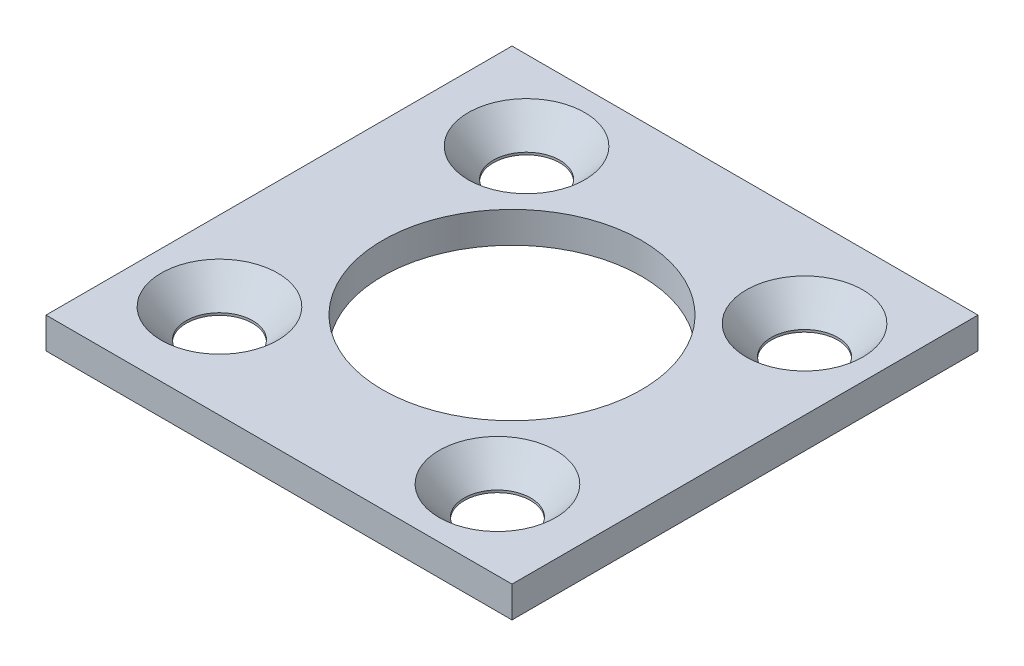
SolidWorks part; units mm, degrees
material "6061-T6 (SS)"
ref_plane "Front Plane" through (0, 0, 0) normal (0, 0, 1) x (1, 0, 0)
ref_plane "Top Plane" through (0, 0, 0) normal (0, 1, 0) x (1, 0, 0)
ref_plane "Right Plane" through (0, 0, 0) normal (1, 0, 0) x (0, 0, -1)
sketch "Sketch1" plane through (0, 0, 0) normal (0, 1, 0) x (1, 0, 0)
  line L1 (0, 0) -> (-22.86, 0)
  line L2 (0, 0) -> (0, 22.86)
  line L3 (0, 22.86) -> (-22.86, 22.86)
  line L4 (-22.86, 0) -> (-22.86, 22.86)
  circle A0 centre (-11.43, 11.43) radius 6.35
  point P9 (-24.5662, 22.7018)
  dimension "D5" = 12.7
  dimension "D1" = 22.86
  dimension "D2" = 22.86
  dimension "D3" = 11.43
  dimension "D4" = 11.43
extrude "Boss-Extrude1" add sketch "Sketch1" along normal blind 1.524
hole_wizard "CSK for #4 Flat Head Machine Screw1" positions "Sketch4" profile "Sketch3" countersink size "#4" standard "ANSI Inch" end condition through all
sketch "Sketch4" plane through (0, 1.524, 0) normal (0, 1, 0) x (1, 0, 0)
  point P0 (-3.8977, 18.2484)
  point P3 (-4.6116, 3.8977)
  point P6 (-18.9623, 4.6116)
  point P9 (-18.2484, 18.9623)
sketch "Sketch3" plane through (-3.8977, 1.524, -18.2484) normal (1, 0, 0) x (0, 0, 1)
  line L0 (0, 0) -> (0, 1.524)
  line L1 (0, 1.524) -> (1.6319, 1.524)
  line L2 (1.6319, 1.524) -> (1.6319, 1.4098)
  line L3 (1.6319, 1.4098) -> (2.8575, 0)
  line L5 (2.8575, 0) -> (0, 0)
  line L6 (-1.6319, 1.4098) -> (-2.8575, 0) construction
  line L11 (0, -6.35) -> (0, 107.95) construction
  dimension "Thru Hole Dia." = 3.2639
  dimension "Thru Hole Depth" = 1.524
  dimension "Near C'Sink Dia." = 5.715
  dimension "Near C'Sink Angle" = 82
equation "\"D3@Sketch1\"=\"D2@Sketch1\"/2"
equation "\"D4@Sketch1\"=\"D1@Sketch1\"/2"
